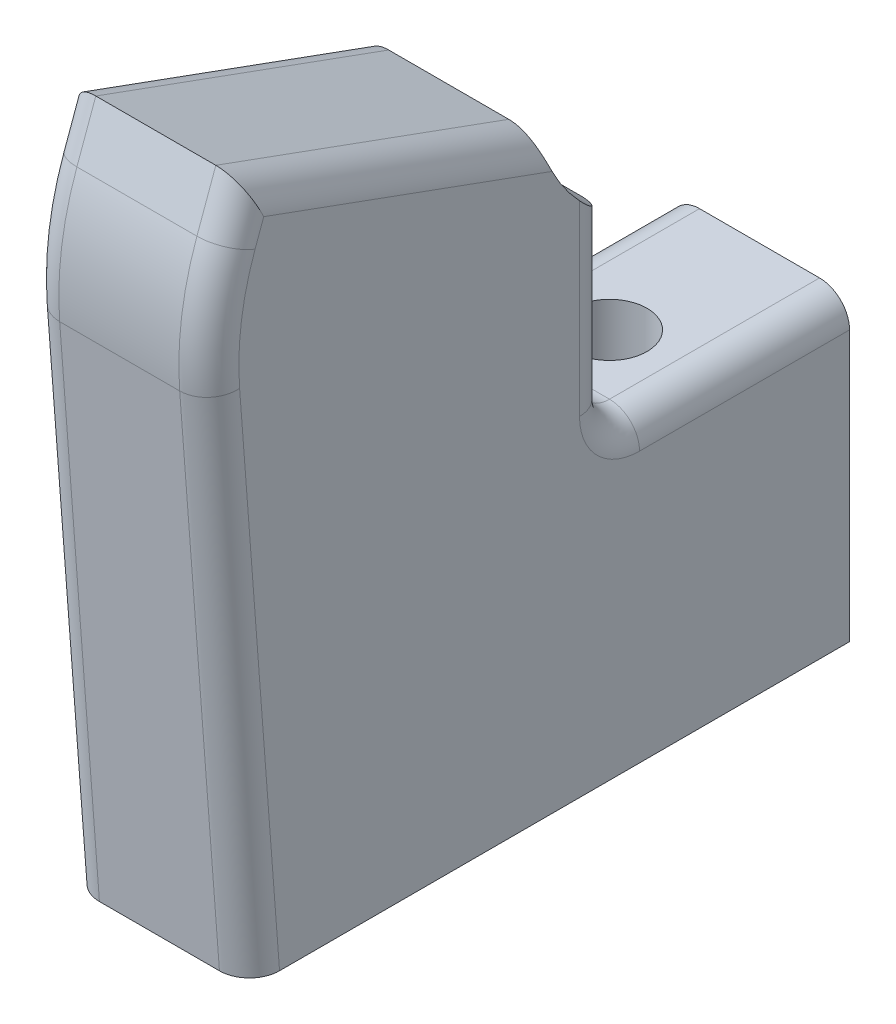
SolidWorks part; units mm, degrees
material "ABS"
ref_plane "Front" through (0, 0, 0) normal (0, 0, 1) x (1, 0, 0)
ref_plane "Top" through (0, 0, 0) normal (0, 1, 0) x (1, 0, 0)
ref_plane "Right" through (0, 0, 0) normal (1, 0, 0) x (0, 0, -1)
sketch "Esquisse1" plane through (0, 0, 0) normal (1, 0, 0) x (0, 0, -1)
  line L0 (0, 0) -> (0, 10)
  line L1 (0, 0) -> (-20, 0)
  line L2 (-20, 0) -> (-21.4895, 19.5525)
  line L3 (-21.4895, 19.5525) -> (-20.1214, 23.3112)
  line L4 (-20.1214, 23.3112) -> (-10.3578, 19.7576)
  line L6 (0, 10) -> (-8, 10)
  line L7 (-8, 10) -> (-8, 16.3902)
  arc A0 (-10.3578, 19.7576) -> (-8, 16.3902) centre (-5, 21) ccw
  dimension "D1" = 3
  dimension "D2" = 21
  dimension "D3" = 5
  dimension "D8" = 5.5
  dimension "D4" = 20
  dimension "D5" = 20
  dimension "D6" = 4
  dimension "D7" = 15
  dimension "D9" = 10
  dimension "D10" = 3
extrude "Boss.-Extru.1" add sketch "Esquisse1" along normal mid plane 6
fillet "Congé1" radius 10 1 edges at (0, 19.5525, 21.4895)
fillet "Congé2" radius 1 1 edges at (0, 10, 8)
fillet "Congé3" radius 1 14 edges at (-3, 19.5211, 21.2615) (-3, 10, 3.5) (-3, 10.2929, 7.7071) (3, 10, 3.5) (3, 10.2929, 7.7071) (3, 19.5211, 21.2615) (-3, 8.7003, 20.6628) (-3, 21.5344, 15.2396) (-3, 13.6951, 8) (3, 13.6951, 8) (3, 21.5344, 15.2396) (3, 8.7003, 20.6628) (-3, 22.4458, 20.4364) (3, 22.4458, 20.4364)
sketch "Esquisse2" plane through (0, 10, 0) normal (0, 1, 0) x (1, 0, 0)
  line L7 (2, 0) -> (-2, 0) construction
  circle A0 centre (0, -5) radius 1.25
  dimension "D2" = 5
  dimension "D1" = 2.5
extrude "Enlèv. mat.-Extru.1" cut sketch "Esquisse2" against normal through all
